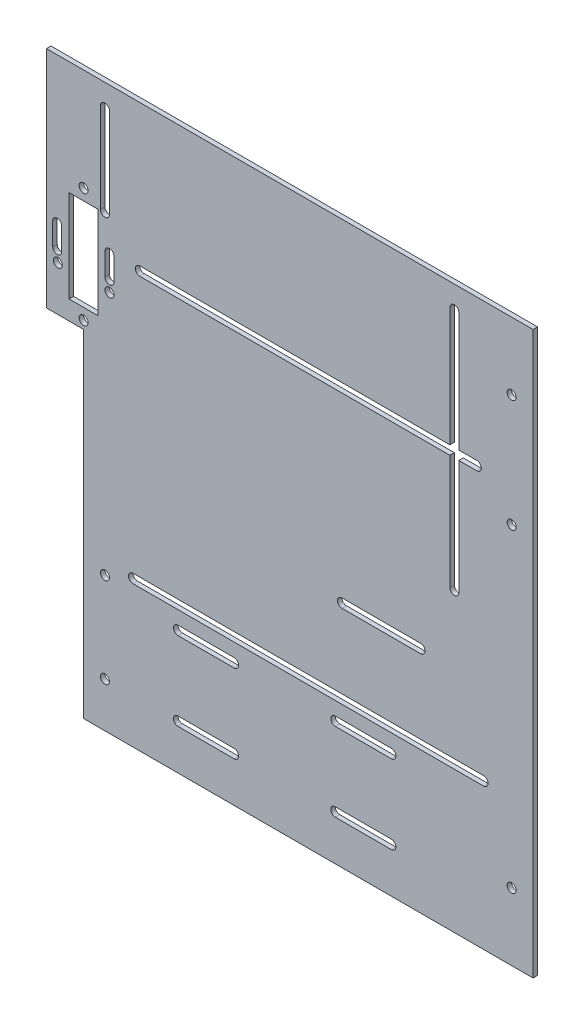
SolidWorks part; units mm, degrees
ref_plane "Front Plane" through (0, 0, 0) normal (0, 0, 1) x (1, 0, 0)
ref_plane "Top Plane" through (0, 0, 0) normal (0, 1, 0) x (1, 0, 0)
ref_plane "Right Plane" through (0, 0, 0) normal (1, 0, 0) x (0, 0, -1)
sketch "Sketch1" plane through (0, 0, 0) normal (0, 0, 1) x (1, 0, 0)
  line L1 (-100, 100) -> (100, 100)
  line L2 (-100, 100) -> (-100, -100)
  line L3 (-100, -100) -> (100, -100)
  line L4 (100, 100) -> (100, -100)
  line L5 (-100, 100) -> (100, -100) construction
  line L6 (-100, -100) -> (100, 100) construction
  point P0 (0, 0)
  dimension "D1" = 200
  dimension "D2" = 200
extrude "Boss-Extrude1" add sketch "Sketch1" along normal blind 2
sketch "Sketch2" plane through (0, 0, 2) normal (0, 0, 1) x (1, 0, 0)
  line L0 (100, -100) -> (100, 100) construction
  line L1 (100, 100) -> (-100, 100) construction
  line L2 (-100, -100) -> (100, -100) construction
  circle A0 centre (90.5, 70) radius 2
  circle A1 centre (90.5, -70) radius 2
  dimension "D1" = 4
  dimension "D4" = 4
  dimension "D2" = 9.5
  dimension "D3" = 30
  dimension "D5" = 9.5
  dimension "D6" = 30
extrude "Cut-Extrude1" cut sketch "Sketch2" against normal blind 13
sketch "Sketch3" plane through (0, 0, 2) normal (0, 0, 1) x (1, 0, 0)
  line L0 (-100, 100) -> (-100, -100) construction
  line L1 (-100, -100) -> (100, -100) construction
  circle A0 centre (-90.5, -40) radius 2
  circle A1 centre (-90.5, -80) radius 2
  dimension "D1" = 4
  dimension "D3" = 9.5
  dimension "D5" = 40
  dimension "D6" = 4
  dimension "D2" = 9.5
  dimension "D4" = 20
extrude "Cut-Extrude2" cut sketch "Sketch3" against normal through all
sketch "Sketch4" plane through (0, 0, 2) normal (0, 0, 1) x (1, 0, 0)
  line L0 (-100, 100) -> (-100, -100) construction
  line L1 (-100, -100) -> (100, -100) construction
  circle A0 centre (-50, -45) radius 2
  circle A1 centre (-50, -80) radius 2
  circle A2 centre (26.5, -45) radius 2
  circle A3 centre (26.5, -80) radius 2
  dimension "D1" = 4
  dimension "D2" = 4
  dimension "D4" = 50
  dimension "D6" = 35
  dimension "D7" = 4
  dimension "D8" = 4
  dimension "D9" = 20
  dimension "D10" = 35
  dimension "D11" = 126.5
  dimension "D3" = 50
  dimension "D5" = 20
  dimension "D12" = 126.5
extrude "Cut-Extrude3" cut sketch "Sketch4" against normal blind 13
sketch "Sketch5" plane through (-100, 0, 0) normal (-1, 0, 0) x (0, 0, 1)
  line L0 (2, 100) -> (2, -100) construction
  line L1 (0, 100) -> (2, 100)
  line L2 (0, 100) -> (0, 50)
  line L3 (0, 50) -> (2, 50)
  line L4 (2, 100) -> (2, 50)
  dimension "D1" = 50
extrude "Boss-Extrude2" add sketch "Sketch5" along normal blind 16.5
sketch "Sketch6" plane through (0, 0, 2) normal (0, 0, 1) x (1, 0, 0)
  line L0 (100, 100) -> (-116.5, 100) construction
  line L1 (-116.5, 50) -> (-116.5, 100) construction
  line L3 (-106.5, 73.5) -> (-93.5, 73.5)
  line L4 (-106.5, 73.5) -> (-106.5, 58.5)
  line L5 (-106.5, 58.5) -> (-93.5, 58.5)
  line L6 (-93.5, 73.5) -> (-93.5, 58.5)
  line L7 (-106.5, 73.5) -> (-93.5, 58.5) construction
  line L8 (-106.5, 58.5) -> (-93.5, 73.5) construction
  circle A0 centre (-111.5, 70) radius 2
  circle A1 centre (-88.5, 70) radius 2
  point P8 (-100, 66)
  dimension "D1" = 4
  dimension "D2" = 4
  dimension "D3" = 30
  dimension "D6" = 23
  dimension "D10" = 11.5
  dimension "D4" = 30
  dimension "D5" = 5
  dimension "D7" = 13
  dimension "D8" = 15
  dimension "D9" = 11.5
extrude "Cut-Extrude4" cut sketch "Sketch6" against normal through all
sketch "Sketch7" plane through (0, 0, 2) normal (0, 0, 1) x (1, 0, 0)
  line L0 (100, 100) -> (-116.5, 100) construction
  line L1 (100, -100) -> (100, 100) construction
  line L2 (-100, -100) -> (100, -100) construction
  line L3 (-100, 50) -> (-100, -100) construction
  circle A0 centre (75, 85) radius 2
  circle A1 centre (78, -35) radius 2
  circle A2 centre (-78, -35) radius 2
  circle A3 centre (-75, 85) radius 2
  dimension "D1" = 4
  dimension "D2" = 15
  dimension "D3" = 25
  dimension "D4" = 4
  dimension "D5" = 22
  dimension "D6" = 65
  dimension "D7" = 4
  dimension "D9" = 65
  dimension "D10" = 4
  dimension "D11" = 15
  dimension "D12" = 25
  dimension "D8" = 22
extrude "Cut-Extrude5" cut sketch "Sketch7" against normal through all
sketch "Sketch8" plane through (0, 0, 2) normal (0, 0, 1) x (1, 0, 0)
  line L0 (65, 95) -> (65, 32) construction
  line L1 (67, 95) -> (67, 32)
  line L2 (63, 95) -> (63, 32)
  line L3 (100, 100) -> (-116.5, 100) construction
  line L4 (100, -100) -> (100, 100) construction
  arc A0 (67, 95) -> (63, 95) centre (65, 95) ccw
  arc A1 (63, 32) -> (67, 32) centre (65, 32) ccw
  point P2 (65, 63.5)
  dimension "D1" = 2
  dimension "D2" = 5
  dimension "D3" = 35
  dimension "D4" = 68
extrude "Cut-Extrude6" cut sketch "Sketch8" against normal blind 10
sketch "Sketch11" plane through (0, 100, 0) normal (0, 1, 0) x (1, 0, 0)
  line L1 (-116.5, -2) -> (100, -2)
  line L2 (-116.5, -2) -> (-116.5, 0)
  line L3 (-116.5, 0) -> (100, 0)
  line L4 (100, -2) -> (100, 0)
extrude "Boss-Extrude3" add sketch "Sketch11" along normal blind 50
sketch "Sketch12" plane through (0, 0, 2) normal (0, 0, 1) x (1, 0, 0)
  line L0 (65, 90.4796) -> (65, 140) construction
  line L1 (63, 90.4796) -> (63, 140)
  line L2 (67, 90.4796) -> (67, 140)
  line L3 (-116.5, 150) -> (100, 150) construction
  arc A0 (63, 90.4796) -> (67, 90.4796) centre (65, 90.4796) ccw
  arc A1 (67, 140) -> (63, 140) centre (65, 140) ccw
  point P3 (65, 115.2398)
  dimension "D1" = 2
  dimension "D2" = 10
extrude "Cut-Extrude8" cut sketch "Sketch12" against normal blind 10
sketch "Sketch15" plane through (0, 0, 2) normal (0, 0, 1) x (1, 0, 0)
  line L0 (-78, -35) -> (78, -35) construction
  line L1 (-78, -33) -> (78, -33)
  line L2 (-78, -37) -> (78, -37)
  arc A0 (-78, -33) -> (-78, -37) centre (-78, -35) ccw
  arc A1 (78, -37) -> (78, -33) centre (78, -35) ccw
  point P4 (0, -35)
  dimension "D1" = 2
extrude "Cut-Extrude9" cut sketch "Sketch15" against normal blind 10
sketch "Sketch16" plane through (0, 0, 2) normal (0, 0, 1) x (1, 0, 0)
  line L0 (-75, 85) -> (75, 85) construction
  line L1 (-75, 87) -> (75, 87)
  line L2 (-75, 83) -> (75, 83)
  arc A0 (-75, 87) -> (-75, 83) centre (-75, 85) ccw
  arc A1 (75, 83) -> (75, 87) centre (75, 85) ccw
  point P4 (0, 85)
  dimension "D1" = 2
extrude "Cut-Extrude10" cut sketch "Sketch16" against normal blind 10
sketch "Sketch17" plane through (0, 0, 2) normal (0, 0, 1) x (1, 0, 0)
  line L0 (100, -100) -> (100, 150) construction
  line L1 (-116.5, 150) -> (100, 150) construction
  circle A0 centre (90.5, 120) radius 2
  dimension "D1" = 4
  dimension "D2" = 9.5
  dimension "D3" = 30
extrude "Cut-Extrude11" cut sketch "Sketch17" against normal blind 10
sketch "Sketch18" plane through (0, 0, 2) normal (0, 0, 1) x (1, 0, 0)
  line L0 (-100, 50) -> (-100, -100) construction
  line L1 (-116.5, 150) -> (100, 150) construction
  circle A0 centre (-90.5, 120) radius 2
  dimension "D1" = 4
  dimension "D2" = 9.5
  dimension "D3" = 30
extrude "Cut-Extrude12" cut sketch "Sketch18" against normal blind 10
sketch "Sketch19" plane through (0, 0, 2) normal (0, 0, 1) x (1, 0, 0)
  line L0 (15, 2) -> (50, 2) construction
  line L1 (15, 4) -> (50, 4)
  line L2 (15, 0) -> (50, 0)
  line L3 (78, -33) -> (-78, -33) construction
  line L4 (100, -100) -> (100, 150) construction
  arc A0 (15, 4) -> (15, 0) centre (15, 2) ccw
  arc A1 (50, 0) -> (50, 4) centre (50, 2) ccw
  point P2 (32.5, 2)
  dimension "D1" = 2
  dimension "D4" = 50
  dimension "D2" = 35
  dimension "D3" = 35
extrude "Cut-Extrude13" cut sketch "Sketch19" against normal blind 10
sketch "Sketch20" plane through (0, 0, 2) normal (0, 0, 1) x (1, 0, 0)
  line L0 (-58, -45) -> (-33, -45) construction
  line L1 (-58, -43) -> (-33, -43)
  line L2 (-58, -47) -> (-33, -47)
  line L3 (-58, -80) -> (-33, -80) construction
  line L4 (-58, -78) -> (-33, -78)
  line L5 (-58, -82) -> (-33, -82)
  line L6 (12, -45) -> (37, -45) construction
  line L7 (12, -43) -> (37, -43)
  line L8 (12, -47) -> (37, -47)
  line L9 (12, -80) -> (37, -80) construction
  line L10 (12, -78) -> (37, -78)
  line L11 (12, -82) -> (37, -82)
  line L12 (-100, 50) -> (-100, -100) construction
  line L13 (100, -100) -> (100, 150) construction
  arc A0 (-58, -43) -> (-58, -47) centre (-58, -45) ccw
  arc A1 (-33, -47) -> (-33, -43) centre (-33, -45) ccw
  arc A2 (-58, -78) -> (-58, -82) centre (-58, -80) ccw
  arc A3 (-33, -82) -> (-33, -78) centre (-33, -80) ccw
  arc A4 (12, -43) -> (12, -47) centre (12, -45) ccw
  arc A5 (37, -47) -> (37, -43) centre (37, -45) ccw
  arc A6 (12, -78) -> (12, -82) centre (12, -80) ccw
  arc A7 (37, -82) -> (37, -78) centre (37, -80) ccw
  point P3 (-45.5, -45)
  point P8 (-45.5, -80)
  point P16 (24.5, -45)
  point P24 (24.5, -80)
  dimension "D1" = 2
  dimension "D2" = 2
  dimension "D3" = 2
  dimension "D4" = 2
  dimension "D9" = 42
  dimension "D10" = 42
  dimension "D11" = 63
  dimension "D12" = 63
  dimension "D5" = 25
  dimension "D6" = 25
  dimension "D7" = 25
  dimension "D8" = 25
extrude "Cut-Extrude14" cut sketch "Sketch20" against normal blind 10
sketch "Sketch21" plane through (0, 0, 2) normal (0, 0, 1) x (1, 0, 0)
  line L0 (-90.5, 140) -> (-90.5, 100) construction
  line L1 (-88.5, 140) -> (-88.5, 100)
  line L2 (-92.5, 140) -> (-92.5, 100)
  line L3 (-116.5, 150) -> (100, 150) construction
  arc A0 (-88.5, 140) -> (-92.5, 140) centre (-90.5, 140) ccw
  arc A1 (-92.5, 100) -> (-88.5, 100) centre (-90.5, 100) ccw
  point P3 (-90.5, 120)
  dimension "D1" = 2
  dimension "D2" = 40
  dimension "D3" = 10
extrude "Cut-Extrude15" cut sketch "Sketch21" against normal blind 10
sketch "Sketch22" plane through (0, 0, 2) normal (0, 0, 1) x (1, 0, 0)
  line L0 (-106.5, 58.5) -> (-93.5, 58.5) construction
  circle A0 centre (-100, 53.5) radius 2
  circle A1 centre (-100, 104.5) radius 2
  circle A2 centre (-111.5, 70) radius 2 construction
  dimension "D1" = 4
  dimension "D2" = 4
  dimension "D3" = 51
  dimension "D4" = 5
  dimension "D5" = 11.5
  dimension "D6" = 11.5
extrude "Cut-Extrude16" cut sketch "Sketch22" against normal blind 10
sketch "Sketch23" plane through (0, 0, 2) normal (0, 0, 1) x (1, 0, 0)
  line L0 (-106.5, 73.5) -> (-93.5, 73.5)
  line L1 (-106.5, 73.5) -> (-106.5, 99.5)
  line L2 (-93.5, 73.5) -> (-93.5, 99.5)
  line L3 (-106.5, 99.5) -> (-93.5, 99.5)
  dimension "D1" = 26
extrude "Cut-Extrude17" cut sketch "Sketch23" against normal blind 10
sketch "Sketch24" plane through (0, 0, 2) normal (0, 0, 1) x (1, 0, 0)
  line L0 (-88.5, 75) -> (-88.5, 85) construction
  line L1 (-90.5, 75) -> (-90.5, 85)
  line L2 (-86.5, 75) -> (-86.5, 85)
  line L3 (-111.7416, 75) -> (-111.7416, 85) construction
  line L4 (-113.7416, 75) -> (-113.7416, 85)
  line L5 (-109.7416, 75) -> (-109.7416, 85)
  arc A0 (-90.5, 75) -> (-86.5, 75) centre (-88.5, 75) ccw
  arc A1 (-86.5, 85) -> (-90.5, 85) centre (-88.5, 85) ccw
  arc A2 (-113.7416, 75) -> (-109.7416, 75) centre (-111.7416, 75) ccw
  arc A3 (-109.7416, 85) -> (-113.7416, 85) centre (-111.7416, 85) ccw
  circle A4 centre (-111.5, 70) radius 2 construction
  circle A5 centre (-88.5, 70) radius 2 construction
  point P3 (-88.5, 80)
  point P8 (-111.7416, 80)
  dimension "D1" = 2
  dimension "D2" = 2
  dimension "D6" = 5
  dimension "D3" = 10
  dimension "D4" = 10
  dimension "D5" = 5
extrude "Cut-Extrude20" cut sketch "Sketch24" against normal blind 10
